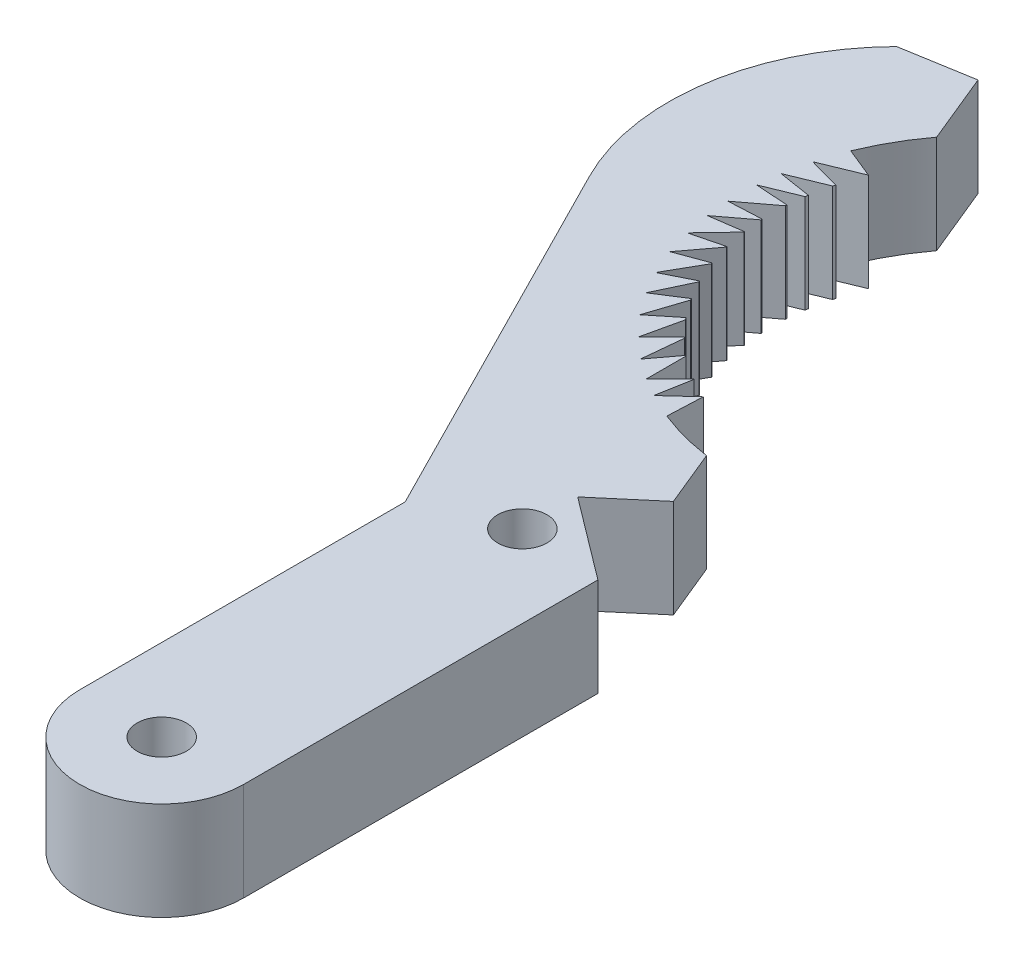
SolidWorks part; units mm, degrees
ref_plane "前视基准面" through (0, 0, 0) normal (0, 0, 1) x (1, 0, 0)
ref_plane "上视基准面" through (0, 0, 0) normal (0, 1, 0) x (1, 0, 0)
ref_plane "右视基准面" through (0, 0, 0) normal (1, 0, 0) x (0, 0, -1)
sketch "草图1" plane through (0, 0, 0) normal (0, 1, 0) x (1, 0, 0)
  line L0 (-9.7379, 0.9473) -> (-9.7379, -18.9027)
  line L1 (0.2621, -18.9027) -> (0.2621, 2.7056)
  line L2 (-18.805, 39.9921) -> (-14.5551, 40.7097)
  line L3 (-8.8757, 14.7802) -> (-7.4221, 16.2338)
  line L4 (-7.3989, 16.2202) -> (-7.7797, 14.1437)
  line L5 (-14.5551, 40.7097) -> (-12.7957, 36.4305)
  line L6 (-4.7379, 6.474) -> (0.2621, 2.7056)
  line L7 (-4.7379, 6.474) -> (-1.5817, 9.1556)
  line L8 (-2.9907, 12.5825) -> (-1.5817, 9.1556)
  line L9 (-7.7797, 14.1437) -> (-6.1972, 15.5944)
  line L10 (-6.1972, 15.5944) -> (-6.2899, 13.4619)
  line L11 (-14.6921, 33.0847) -> (-12.8686, 32.3413)
  line L12 (-12.8686, 32.3413) -> (-15.2785, 31.3505)
  line L13 (-15.2785, 31.3505) -> (-13.3483, 30.8267)
  line L14 (-13.3887, 30.6743) -> (-15.6192, 29.7572)
  line L15 (-15.6192, 29.7572) -> (-13.6436, 29.4458)
  line L16 (-13.6694, 29.2743) -> (-15.7694, 28.4109)
  line L17 (-15.7694, 28.4109) -> (-13.7738, 28.2791)
  line L18 (-13.7791, 28.1942) -> (-15.7836, 26.6781)
  line L19 (-15.7836, 26.6781) -> (-13.7861, 26.7773)
  line L20 (-13.7821, 26.7021) -> (-15.6497, 25.2895)
  line L21 (-15.6497, 25.2895) -> (-13.67, 25.5739)
  line L22 (-13.6638, 25.5313) -> (-15.3493, 23.7643)
  line L23 (-15.3493, 23.7643) -> (-13.4097, 24.252)
  line L24 (-13.3997, 24.2125) -> (-14.8794, 22.2424)
  line L25 (-14.8794, 22.2424) -> (-13.0024, 22.933)
  line L26 (-12.9808, 22.8747) -> (-14.2151, 20.7071)
  line L27 (-14.2151, 20.7071) -> (-12.4267, 21.6024)
  line L28 (-12.3979, 21.5453) -> (-13.4379, 19.3389)
  line L29 (-13.4379, 19.3389) -> (-11.7531, 20.4167)
  line L30 (-11.6942, 20.3255) -> (-12.4669, 17.9916)
  line L31 (-12.4669, 17.9916) -> (-10.9116, 19.249)
  line L32 (-10.8087, 19.1234) -> (-11.3425, 16.7496)
  line L33 (-11.3425, 16.7496) -> (-9.9371, 18.1726)
  line L34 (-9.8648, 18.1017) -> (-10.1093, 15.6587)
  line L35 (-10.1093, 15.6587) -> (-8.9078, 17.2585)
  line L36 (-8.8757, 17.233) -> (-8.8757, 14.7802)
  line L37 (-9.7379, 0.9473) -> (-21.3157, 23.7643)
  line L38 (-13.7861, 26.7773) -> (-13.7821, 26.7021)
  arc A0 (-9.7379, -18.9027) -> (0.2621, -18.9027) centre (-4.7379, -18.9027) ccw
  circle A1 centre (-4.7379, -18.9027) radius 1.5
  circle A2 centre (-4.7379, 3.0973) radius 1.5
  arc A3 (-12.7957, 36.4305) -> (-14.6921, 33.0847) centre (-0.8021, 27.422) ccw
  arc A4 (-13.3483, 30.8267) -> (-13.3887, 30.6743) centre (-0.8021, 27.422) ccw
  arc A5 (-13.4097, 24.252) -> (-13.3997, 24.2125) centre (-0.8021, 27.422) ccw
  arc A6 (-7.4221, 16.2338) -> (-7.3989, 16.2202) centre (-0.8021, 27.422) ccw
  arc A7 (-8.9078, 17.2585) -> (-8.8757, 17.233) centre (-0.8021, 27.422) ccw
  arc A8 (-9.9371, 18.1726) -> (-9.8648, 18.1017) centre (-0.8021, 27.422) ccw
  arc A9 (-10.9116, 19.249) -> (-10.8087, 19.1234) centre (-0.8021, 27.422) ccw
  arc A10 (-11.7531, 20.4167) -> (-11.6942, 20.3255) centre (-0.8021, 27.422) ccw
  arc A11 (-12.4267, 21.6024) -> (-12.3979, 21.5453) centre (-0.8021, 27.422) ccw
  arc A12 (-13.0024, 22.933) -> (-12.9808, 22.8747) centre (-0.8021, 27.422) ccw
  arc A13 (-13.67, 25.5739) -> (-13.6638, 25.5313) centre (-0.8021, 27.422) ccw
  arc A14 (-13.7738, 28.2791) -> (-13.7791, 28.1942) centre (-0.8021, 27.422) ccw
  arc A15 (-13.6436, 29.4458) -> (-13.6694, 29.2743) centre (-0.8021, 27.422) ccw
  arc A16 (-6.2899, 13.4619) -> (-2.9907, 12.5825) centre (-0.8021, 27.422) ccw
  arc A17 (-21.3157, 23.7643) -> (-18.805, 39.9921) centre (-8.7682, 30.1312) cw
  dimension "D1" = 19.85
  dimension "D2" = 4.31
extrude "凸台-拉伸1" add sketch "草图1" along normal blind 6
